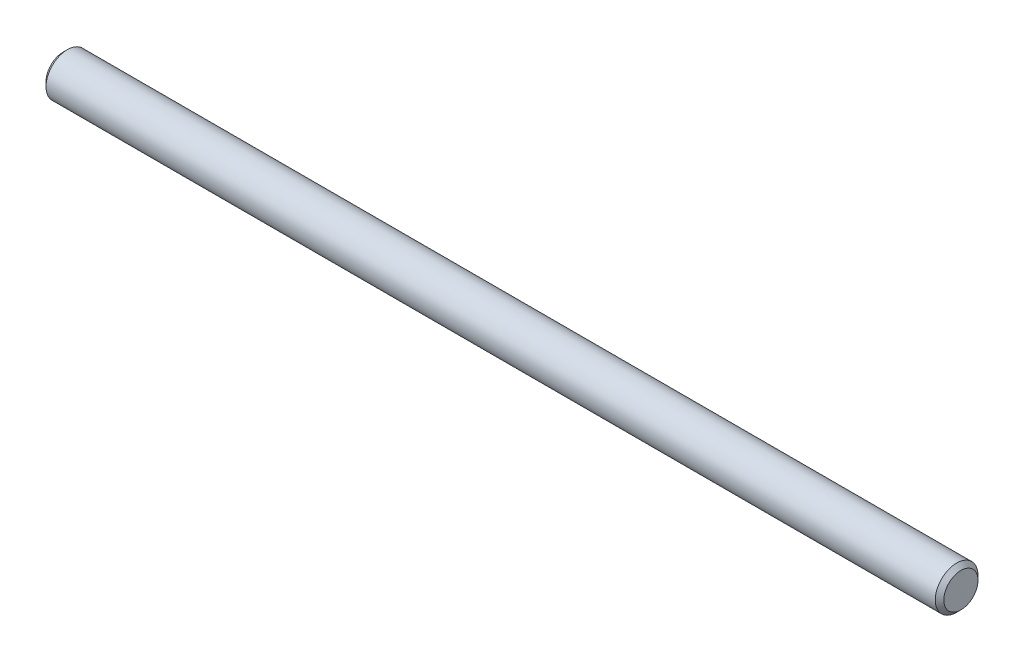
SolidWorks part; units mm, degrees
material "1.4305 (X8CrNiS18-9)"
ref_plane "Ebene vorne" through (0, 0, 0) normal (0, 0, 1) x (1, 0, 0)
ref_plane "Ebene oben" through (0, 0, 0) normal (0, 1, 0) x (1, 0, 0)
ref_plane "Ebene rechts" through (0, 0, 0) normal (1, 0, 0) x (0, 0, -1)
sketch "Skizze1" plane through (0, 0, 0) normal (1, 0, 0) x (0, 0, -1)
  circle A0 centre (0, 0) radius 1
  dimension "D1" = 2
extrude "Aufsatz-Linear austragen1" add sketch "Skizze1" along normal blind 42
chamfer "Fase1" distance 0.2 angle 45 2 edges at (0, 0, -1) (42, 0, -1)
